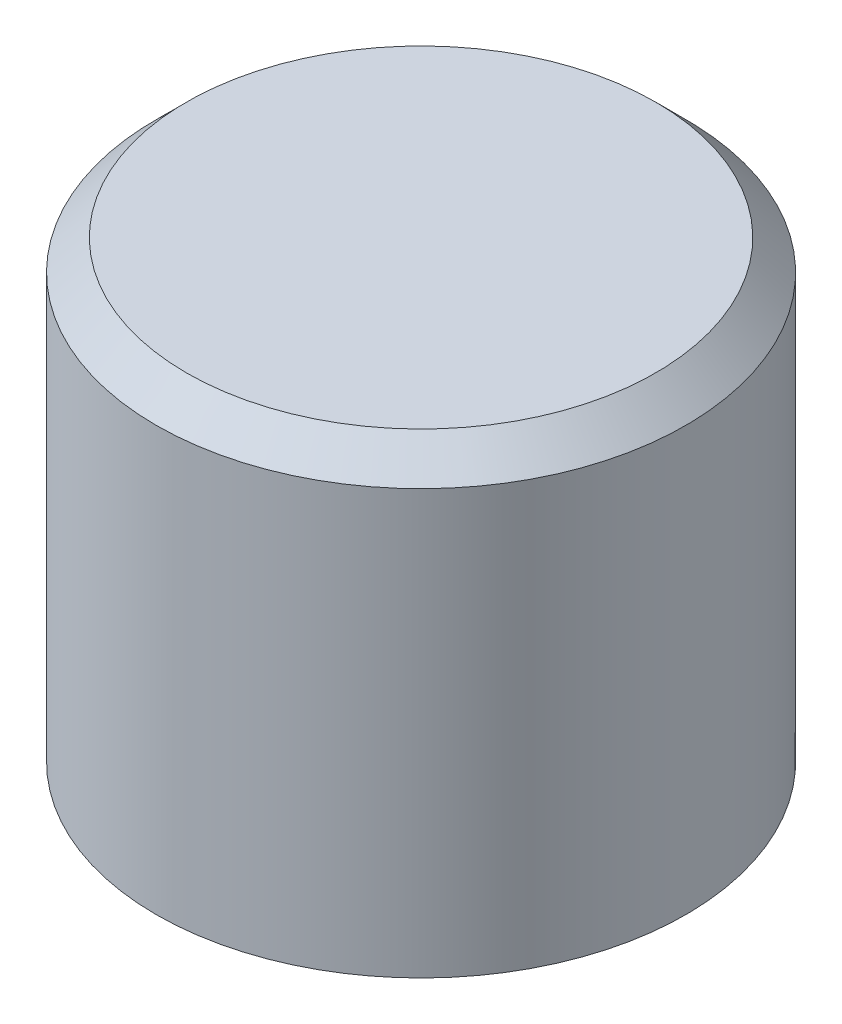
SolidWorks part; units mm, degrees
ref_plane "Front Plane" through (0, 0, 0) normal (0, 0, 1) x (1, 0, 0)
ref_plane "Top Plane" through (0, 0, 0) normal (0, 1, 0) x (1, 0, 0)
ref_plane "Right Plane" through (0, 0, 0) normal (1, 0, 0) x (0, 0, -1)
sketch "Sketch1" plane through (0, 0, 0) normal (0, 1, 0) x (1, 0, 0)
  circle A0 centre (0, 0) radius 8.75
  dimension "D1" = 17.5
extrude "Boss-Extrude1" add sketch "Sketch1" along normal blind 15
sketch "Sketch2" plane through (0, 0, 0) normal (0, -1, 0) x (1, 0, 0)
  circle A0 centre (0, 0) radius 7
extrude "Cut-Extrude1" cut sketch "Sketch2" against normal blind 8
sketch "Sketch3" plane through (0, 8, 0) normal (0, -1, 0) x (1, 0, 0)
  line L0 (-2.75, 1.7321) -> (2.75, 1.7321)
  arc A0 (-2.75, 1.7321) -> (2.75, 1.7321) centre (0, 0) ccw
  dimension "D1" = 5.5
  dimension "D2" = 6.5
extrude "Cut-Extrude2" cut sketch "Sketch3" against normal offset from surface (5.5 mm away) 1.5 up to face at (0, 15, 8.75)
chamfer "Chamfer1" distance 1 angle 45 1 edges at (0, 15, 8.75)
chamfer "Chamfer2" distance 1 angle 45 2 edges at (0, 8, -3.25) (0, 8, 1.7321)
